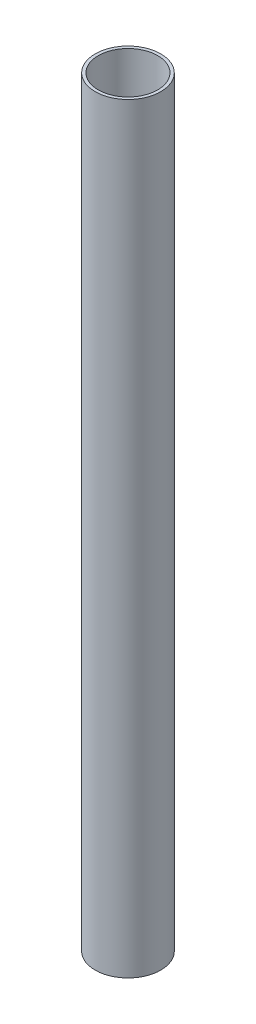
SolidWorks part; units mm, degrees
ref_plane "Front Plane" through (0, 0, 0) normal (0, 0, 1) x (1, 0, 0)
ref_plane "Top Plane" through (0, 0, 0) normal (0, 1, 0) x (1, 0, 0)
ref_plane "Right Plane" through (0, 0, 0) normal (1, 0, 0) x (0, 0, -1)
sketch "Sketch1" plane through (0, 0, 0) normal (0, 1, 0) x (1, 0, 0)
  circle A0 centre (0, 0) radius 0.56
  circle A1 centre (0, 0) radius 0.508
extrude "Boss-Extrude1" add sketch "Sketch1" along normal blind 13
